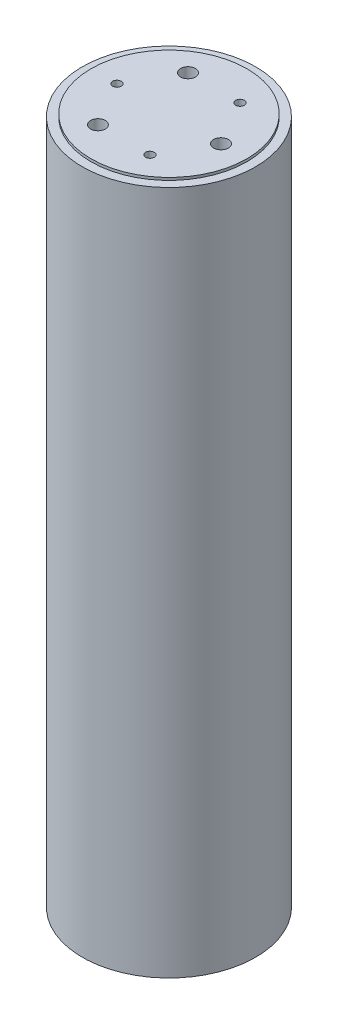
SolidWorks part; units mm, degrees
ref_plane "Спереди" through (0, 0, 0) normal (0, 0, 1) x (1, 0, 0)
ref_plane "Сверху" through (0, 0, 0) normal (0, 1, 0) x (1, 0, 0)
ref_plane "Справа" through (0, 0, 0) normal (1, 0, 0) x (0, 0, -1)
sketch "Эскиз2" plane through (0, 0, 0) normal (1, 0, 0) x (0, 0, -1)
  line L0 (0, 0) -> (0, 396.5) construction
  line L1 (45, 1.5) -> (50, 1.5)
  line L2 (50, 1.5) -> (50, 396.5)
  line L3 (50, 396.5) -> (0, 396.5)
  line L4 (0, 388.5) -> (48, 388.5)
  line L5 (48, 388.5) -> (48, 9.5)
  line L6 (48, 9.5) -> (0, 9.5)
  line L7 (0, 0) -> (45, 0)
  line L8 (45, 0) -> (45, 1.5)
  line L9 (0, 388.5) -> (0, 396.5)
  line L10 (0, 9.5) -> (0, 0)
  dimension "D1" = 395
  dimension "D2" = 96
  dimension "D3" = 100
  dimension "D4" = 9.5
  dimension "D5" = 8
  dimension "D6" = 8
  dimension "D7" = 90
revolve "Повернуть2" add sketch "Эскиз2" angle 360 about L0
sketch "Эскиз5" plane through (0, 0, 0) normal (0, -1, 0) x (1, 0, 0)
  line L0 (0, 0) -> (62.4818, 0) construction
  circle A0 centre (0, 0) radius 5.7
  circle A1 centre (0, 0) radius 30 construction
  circle A2 centre (30, 0) radius 4.28
  dimension "D1" = 11.4
  dimension "D2" = 8.56
  dimension "D3" = 60
extrude "Вырез-Вытянуть4" cut sketch "Эскиз5" against normal blind 33
sketch "Эскиз6" plane through (0, 0, 0) normal (0, -1, 0) x (1, 0, 0)
  circle A0 centre (0, 0) radius 30 construction
  circle A1 centre (-30, 0) radius 2.5
  circle A2 centre (15, 25.9808) radius 2.5
  circle A3 centre (15, -25.9808) radius 2.5
  point P12 (0, 0)
  dimension "D1" = 60
  dimension "D2" = 5
  dimension "D3" = 3
extrude "Вырез-Вытянуть5" cut sketch "Эскиз6" against normal blind 5
chamfer "Фаска2" distance 2.2 angle 45 1 edges at (0, 0, -5.7)
sketch "Эскиз7" plane through (0, 396.5, 0) normal (0, 1, 0) x (1, 0, 0)
  circle A0 centre (0, 0) radius 45
  dimension "D1" = 90
extrude "Бобышка-Вытянуть1" add sketch "Эскиз7" along normal blind 1.5 contours A0
sketch "Эскиз8" plane through (0, 398, 0) normal (0, 1, 0) x (1, 0, 0)
  line L0 (0, 0) -> (-59.3108, 0) construction
  circle A0 centre (0, 0) radius 30 construction
  circle A1 centre (-30, 0) radius 2.5
  circle A2 centre (15, 25.9808) radius 2.5
  circle A3 centre (0, 0) radius 30 construction
  circle A4 centre (15, -25.9808) radius 2.5
  circle A5 centre (0, 0) radius 30 construction
  point P15 (0, 0)
  dimension "D1" = 60
  dimension "D2" = 5
  dimension "D3" = 3
extrude "Вырез-Вытянуть6" cut sketch "Эскиз8" against normal blind 5
sketch "Эскиз9" plane through (0, 398, 0) normal (0, 1, 0) x (1, 0, 0)
  line L0 (0, 0) -> (30, 0) construction
  circle A0 centre (0, 0) radius 30 construction
  circle A1 centre (30, 0) radius 4.28
  circle A2 centre (-15, -25.9808) radius 4.28
  circle A3 centre (-15, 25.9808) radius 4.28
  point P13 (0, 0)
  dimension "D1" = 8.56
  dimension "D2" = 3
extrude "Вырез-Вытянуть7" cut sketch "Эскиз9" against normal blind 85
